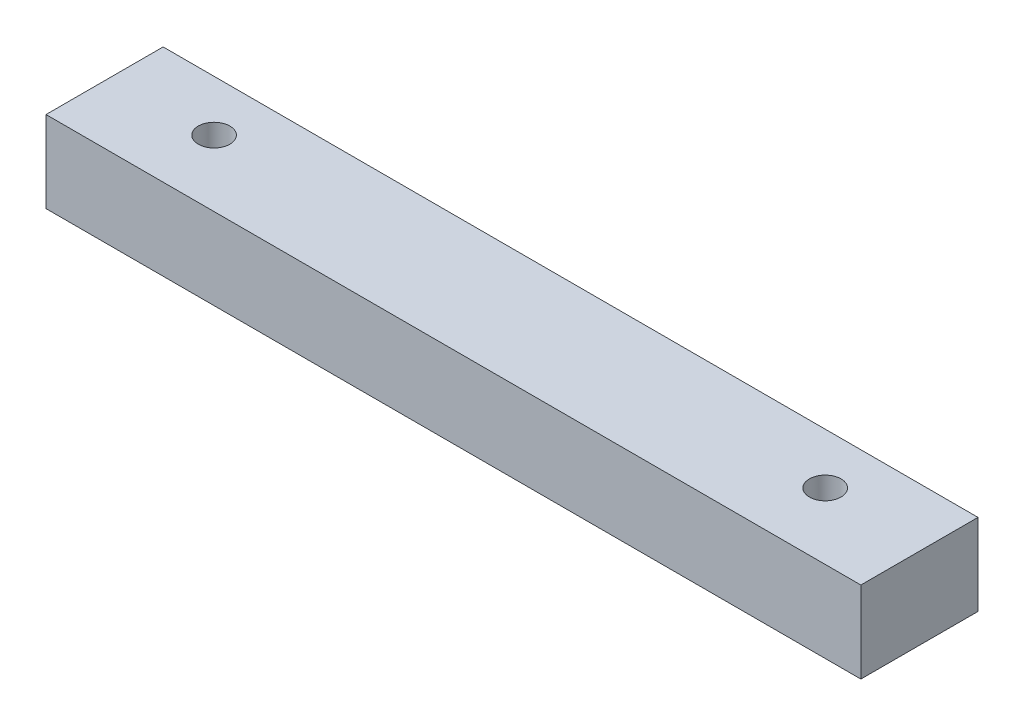
SolidWorks part; units mm, degrees
ref_plane "前视基准面" through (0, 0, 0) normal (0, 0, 1) x (1, 0, 0)
ref_plane "上视基准面" through (0, 0, 0) normal (0, 1, 0) x (1, 0, 0)
ref_plane "右视基准面" through (0, 0, 0) normal (1, 0, 0) x (0, 0, -1)
other "Configuration Table"
sketch "草图1" plane through (0, 0, 0) normal (0, 0, 1) x (1, 0, 0)
  line L1 (0, 0) -> (80, 0)
  line L2 (0, 0) -> (0, 8)
  line L3 (0, 8) -> (80, 8)
  line L4 (80, 0) -> (80, 8)
  dimension "D1" = 80
  dimension "D2" = 8
extrude "凸台-拉伸1" add sketch "草图1" along normal blind 11.5
sketch "草图2" plane through (0, 8, 0) normal (0, 1, 0) x (1, 0, 0)
  line L0 (40, 0) -> (40, -9.3606) construction
  line L1 (80, 0) -> (0, 0) construction
  circle A0 centre (10, -5) radius 1.55
  circle A1 centre (70, -5) radius 1.55
  dimension "D1" = 3.1
  dimension "D2" = 5
  dimension "D3" = 30
extrude "切除-拉伸1" cut sketch "草图2" against normal up to next
